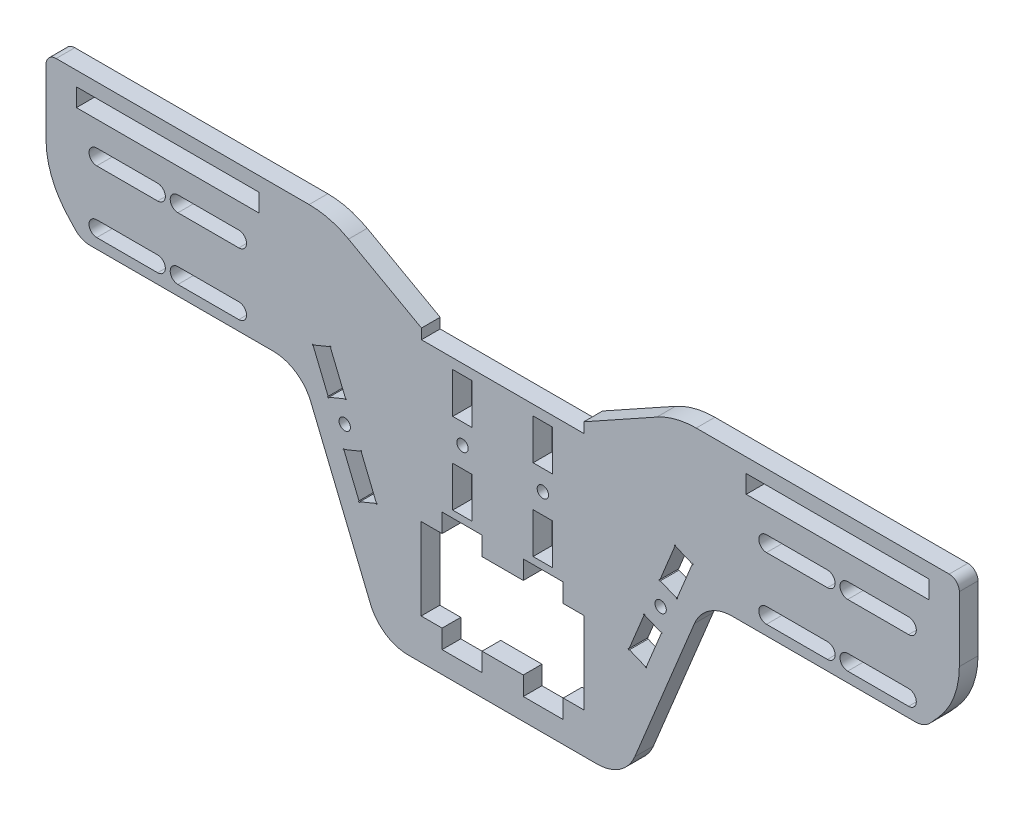
SolidWorks part; units mm, degrees
ref_plane "Front Plane" through (0, 0, 0) normal (0, 0, 1) x (1, 0, 0)
ref_plane "Top Plane" through (0, 0, 0) normal (0, 1, 0) x (1, 0, 0)
ref_plane "Right Plane" through (0, 0, 0) normal (1, 0, 0) x (0, 0, -1)
sketch "Sketch1" plane through (0, 0, 0) normal (0, 0, 1) x (1, 0, 0)
  line L0 (0, 0) -> (0, 65.275) construction
  line L1 (6.45, -12.8) -> (-6.45, -12.8)
  line L2 (12.7, -12.8) -> (12.7, -18.642) construction
  line L3 (6.45, 12.8) -> (-6.45, 12.8)
  line L4 (-25.5, -12.8) -> (-25.5, -6.25)
  line L5 (0, 12.8) -> (0, -12.8) construction
  line L6 (25.5, 0) -> (-25.5, 0) construction
  line L7 (25.4, 65.275) -> (53.975, 81.1576)
  line L8 (63.246, -20.4246) -> (127.254, -20.4246) construction
  line L9 (63.246, 24.6858) -> (127.254, 24.6858) construction
  line L10 (38.0999, -25.3999) -> (-38.0999, -25.3999)
  line L11 (95.25, 65.275) -> (-95.25, 65.275) construction
  line L12 (-95.25, 65.275) -> (-127, 65.275) construction
  line L13 (95.25, 65.275) -> (127, 65.275) construction
  line L14 (117.475, 103.375) -> (-117.475, 103.375) construction
  line L15 (95.25, 62.1) -> (-95.25, 62.1) construction
  line L16 (-171.45, 87.5) -> (-19.05, 87.5) construction
  line L17 (-171.45, 87.5) -> (-171.45, 119.25) construction
  line L18 (-171.45, 119.25) -> (-19.05, 119.25) construction
  line L19 (-19.05, 87.5) -> (-19.05, 119.25) construction
  line L20 (-95.25, 119.25) -> (-95.25, 87.5) construction
  line L21 (-171.45, 103.375) -> (-19.05, 103.375) construction
  line L22 (-18.95, 12.8) -> (-25.5, 12.8)
  line L23 (-6.45, 18.642) -> (-18.95, 18.642)
  line L24 (-6.45, 18.642) -> (-6.45, 12.8)
  line L25 (-25.5, 6.25) -> (-25.5, 12.8)
  line L26 (-18.95, 18.642) -> (-18.95, 12.8)
  line L27 (-12.7, 12.8) -> (-12.7, 18.642) construction
  line L28 (-6.45, 15.721) -> (-18.95, 15.721) construction
  line L29 (-31.342, -6.25) -> (-25.5, -6.25)
  line L30 (25.5, 12.8) -> (-25.5, 12.8) construction
  line L31 (-31.342, -6.25) -> (-31.342, 6.25)
  line L32 (-31.342, 6.25) -> (-25.5, 6.25)
  line L33 (-6.45, -15.721) -> (-18.95, -15.721) construction
  line L34 (-28.421, 6.25) -> (-28.421, -6.25) construction
  line L35 (-31.342, 0) -> (-25.5, 0) construction
  line L36 (-12.7, -12.8) -> (-12.7, -18.642) construction
  line L37 (-25.5, -12.8) -> (-25.5, 12.8) construction
  line L38 (-18.95, -18.642) -> (-18.95, -12.8)
  line L39 (-6.45, -18.642) -> (-6.45, -12.8)
  line L40 (-6.45, -18.642) -> (-18.95, -18.642)
  line L41 (-18.95, -12.8) -> (-25.5, -12.8)
  line L42 (31.342, 0) -> (25.5, 0) construction
  line L43 (25.5, -12.8) -> (-25.5, -12.8) construction
  line L44 (25.5, -12.8) -> (25.5, 12.8) construction
  line L45 (28.421, 6.25) -> (28.421, -6.25) construction
  line L46 (6.45, -15.721) -> (18.95, -15.721) construction
  line L47 (6.45, 15.721) -> (18.95, 15.721) construction
  line L48 (12.7, 12.8) -> (12.7, 18.642) construction
  line L49 (18.95, -12.8) -> (25.5, -12.8)
  line L50 (6.45, -18.642) -> (18.95, -18.642)
  line L51 (6.45, -18.642) -> (6.45, -12.8)
  line L52 (18.95, -18.642) -> (18.95, -12.8)
  line L53 (31.342, 6.25) -> (25.5, 6.25)
  line L54 (31.342, -6.25) -> (31.342, 6.25)
  line L55 (31.342, -6.25) -> (25.5, -6.25)
  line L56 (18.95, 18.642) -> (18.95, 12.8)
  line L57 (25.5, 6.25) -> (25.5, 12.8)
  line L58 (6.45, 18.642) -> (6.45, 12.8)
  line L59 (6.45, 18.642) -> (18.95, 18.642)
  line L60 (18.95, 12.8) -> (25.5, 12.8)
  line L61 (25.5, -12.8) -> (25.5, -6.25)
  line L62 (-82.55, 60.83) -> (-107.95, 60.83) construction
  line L63 (-88.9, 71.0154) -> (-101.6, 71.0154) construction
  line L64 (-88.9, 71.0154) -> (-88.9, 112.9) construction
  line L65 (-88.9, 112.9) -> (-101.6, 112.9) construction
  line L66 (-101.6, 71.0154) -> (-101.6, 112.9) construction
  line L67 (-95.25, 112.9) -> (-95.25, 71.0154) construction
  line L68 (-88.9, 91.9577) -> (-101.6, 91.9577) construction
  line L69 (-82.55, 60.83) -> (-101.6, 60.83) construction
  line L70 (-82.55, 58.417) -> (-101.6, 58.417)
  line L71 (-82.55, 63.243) -> (-101.6, 63.243)
  line L72 (-107.95, 60.83) -> (-127, 60.83) construction
  line L73 (-107.95, 58.417) -> (-127, 58.417)
  line L74 (-107.95, 63.243) -> (-127, 63.243)
  line L75 (-95.25, 73.8364) -> (-114.3, 73.8364) construction
  line L76 (74.2442, 71.0154) -> (116.2558, 71.0154) construction
  line L77 (-76.2, 71.0154) -> (-133.35, 71.0154)
  line L78 (-76.2, 71.0154) -> (-76.2, 76.6574)
  line L79 (-76.2, 76.6574) -> (-133.35, 76.6574)
  line L80 (-123.825, 70.9654) -> (-123.825, 76.7074) construction
  line L81 (-107.95, 73.8364) -> (-139.7, 73.8364) construction
  line L82 (-133.35, 71.0154) -> (-133.35, 76.6574)
  line L83 (-104.775, 76.6574) -> (-104.775, 71.0154) construction
  line L84 (-76.2, 73.8364) -> (-133.35, 73.8364) construction
  line L85 (76.2, 73.8364) -> (133.35, 73.8364) construction
  line L86 (104.775, 76.6574) -> (104.775, 71.0154) construction
  line L87 (107.95, 73.8364) -> (139.7, 73.8364) construction
  line L88 (123.825, 70.9654) -> (123.825, 76.7074) construction
  line L89 (95.25, 73.8364) -> (114.3, 73.8364) construction
  line L90 (-82.55, 41.399) -> (-101.6, 41.399) construction
  line L91 (-82.55, 38.986) -> (-101.6, 38.986)
  line L92 (-82.55, 43.812) -> (-101.6, 43.812)
  line L93 (-107.95, 41.399) -> (-127, 41.399) construction
  line L94 (-107.95, 38.986) -> (-127, 38.986)
  line L95 (-107.95, 43.812) -> (-127, 43.812)
  line L96 (25.4, 62.1) -> (-25.4, 62.1)
  line L97 (-74.2442, 24.6858) -> (-116.2558, 24.6858) construction
  line L98 (-74.2442, 24.6858) -> (-74.2442, 71.0154) construction
  line L99 (-74.2442, 71.0154) -> (-116.2558, 71.0154) construction
  line L100 (-116.2558, 24.6858) -> (-116.2558, 71.0154) construction
  line L101 (-95.25, 71.0154) -> (-95.25, 24.6858) construction
  line L102 (-74.2442, 47.8506) -> (-116.2558, 47.8506) construction
  line L103 (-63.246, -65.535) -> (-127.254, -65.535) construction
  line L104 (-63.246, -65.535) -> (-63.246, 24.6858) construction
  line L105 (-63.246, 24.6858) -> (-127.254, 24.6858) construction
  line L106 (-127.254, -65.535) -> (-127.254, 24.6858) construction
  line L107 (-95.25, 24.6858) -> (-95.25, -65.535) construction
  line L108 (-63.246, -20.4246) -> (-127.254, -20.4246) construction
  line L109 (-25.4, 62.1) -> (-25.4, 65.275)
  line L110 (-38.0999, -25.3999) -> (-63.246, 35.811)
  line L111 (-63.246, 35.811) -> (-131.9276, 35.811)
  line L112 (-142.875, 81.1576) -> (-142.875, 47.8506)
  line L113 (-131.9276, 35.811) -> (-142.875, 47.8506)
  line L114 (-142.875, 81.1576) -> (-53.975, 81.1576)
  line L115 (-25.4, 65.275) -> (-53.975, 81.1576)
  line L116 (74.2442, 47.8506) -> (116.2558, 47.8506) construction
  line L117 (38.0999, 25.3999) -> (-38.0999, 25.3999) construction
  line L118 (-38.0999, -25.3999) -> (-38.0999, 25.3999) construction
  line L119 (38.0999, -25.3999) -> (38.0999, 25.3999) construction
  line L120 (95.25, 71.0154) -> (95.25, 24.6858) construction
  line L121 (116.2558, 24.6858) -> (116.2558, 71.0154) construction
  line L122 (88.9, 71.0154) -> (101.6, 71.0154) construction
  line L123 (74.2442, 24.6858) -> (74.2442, 71.0154) construction
  line L124 (74.2442, 24.6858) -> (116.2558, 24.6858) construction
  line L125 (133.35, 71.0154) -> (133.35, 76.6574)
  line L126 (76.2, 76.6574) -> (133.35, 76.6574)
  line L127 (76.2, 71.0154) -> (76.2, 76.6574)
  line L128 (76.2, 71.0154) -> (133.35, 71.0154)
  line L129 (82.55, 60.83) -> (107.95, 60.83) construction
  line L130 (95.25, 65.275) -> (127, 65.275) construction
  line L131 (142.875, 81.1576) -> (53.975, 81.1576)
  line L132 (131.9276, 35.811) -> (142.875, 47.8506)
  line L133 (142.875, 81.1576) -> (142.875, 47.8506)
  line L134 (63.246, 35.811) -> (131.9276, 35.811)
  line L135 (38.0999, -25.3999) -> (63.246, 35.811)
  line L148 (107.95, 41.399) -> (127, 41.399) construction
  line L149 (107.95, 38.986) -> (127, 38.986)
  line L150 (107.95, 43.812) -> (127, 43.812)
  line L151 (82.55, 41.399) -> (101.6, 41.399) construction
  line L152 (82.55, 38.986) -> (101.6, 38.986)
  line L153 (82.55, 43.812) -> (101.6, 43.812)
  line L154 (107.95, 60.83) -> (127, 60.83) construction
  line L155 (107.95, 58.417) -> (127, 58.417)
  line L156 (107.95, 63.243) -> (127, 63.243)
  line L157 (82.55, 60.83) -> (101.6, 60.83) construction
  line L158 (82.55, 58.417) -> (101.6, 58.417)
  line L159 (82.55, 63.243) -> (101.6, 63.243)
  line L160 (25.4, 62.1) -> (25.4, 65.275)
  circle A0 centre (0, 103.375) radius 38.1 construction
  arc A1 (-82.55, 58.417) -> (-82.55, 63.243) centre (-82.55, 60.83) ccw
  arc A2 (-101.6, 63.243) -> (-101.6, 58.417) centre (-101.6, 60.83) ccw
  arc A3 (-107.95, 58.417) -> (-107.95, 63.243) centre (-107.95, 60.83) ccw
  arc A4 (-127, 63.243) -> (-127, 58.417) centre (-127, 60.83) ccw
  arc A5 (-82.55, 38.986) -> (-82.55, 43.812) centre (-82.55, 41.399) ccw
  arc A6 (-101.6, 43.812) -> (-101.6, 38.986) centre (-101.6, 41.399) ccw
  arc A7 (-107.95, 38.986) -> (-107.95, 43.812) centre (-107.95, 41.399) ccw
  arc A8 (-127, 43.812) -> (-127, 38.986) centre (-127, 41.399) ccw
  arc A9 (107.95, 38.986) -> (107.95, 43.812) centre (107.95, 41.399) cw
  arc A10 (127, 43.812) -> (127, 38.986) centre (127, 41.399) cw
  arc A11 (82.55, 38.986) -> (82.55, 43.812) centre (82.55, 41.399) cw
  arc A12 (101.6, 43.812) -> (101.6, 38.986) centre (101.6, 41.399) cw
  arc A13 (107.95, 58.417) -> (107.95, 63.243) centre (107.95, 60.83) cw
  arc A14 (127, 63.243) -> (127, 58.417) centre (127, 60.83) cw
  arc A15 (82.55, 58.417) -> (82.55, 63.243) centre (82.55, 60.83) cw
  arc A16 (101.6, 63.243) -> (101.6, 58.417) centre (101.6, 60.83) cw
  ellipse E0 centre (0, 103.375) end of major axis (0, 141.475) minor radius 19.05 construction
  point P0 (0, 0)
  point P9 (0, -25.3999)
  point P13 (0, 65.275)
  point P31 (0, 103.375)
  point P32 (-95.25, 103.375)
  point P38 (-12.7, 15.721)
  point P42 (-28.421, 0)
  point P54 (-12.7, -15.721)
  point P79 (12.7, -15.721)
  point P80 (28.421, 0)
  point P81 (12.7, 15.721)
  point P85 (-95.25, 91.9577)
  point P95 (-92.075, 60.83)
  point P98 (-95.25, 60.83)
  point P109 (-117.475, 60.83)
  point P110 (-123.825, 73.8364)
  point P117 (-104.775, 73.8364)
  point P122 (-104.775, 73.8864)
  point P124 (-92.075, 41.399)
  point P125 (-95.25, 47.8506)
  point P128 (-82.423, 73.8364)
  point P150 (-117.475, 41.399)
  point P160 (-95.25, -20.4246)
  point P193 (82.423, 73.8364)
  point P194 (104.775, 73.8864)
  point P201 (104.775, 73.8364)
  point P202 (123.825, 73.8364)
  point P213 (95.25, -20.4246)
  point P220 (117.475, 41.399)
  point P226 (95.25, 47.8506)
  point P233 (92.075, 41.399)
  point P241 (117.475, 60.83)
  point P246 (95.25, 60.83)
  point P248 (92.075, 60.83)
  point P255 (0, 62.1)
  dimension "D7" = 76.2
  dimension "D25" = 57.15
  dimension "D18" = 2.413
  dimension "D27" = 2
  dimension "D1" = 51
  dimension "D2" = 25.6
  dimension "D3" = 65.275
  dimension "D4" = 12.5999
  dimension "D5" = 190.5
  dimension "D6" = 31.75
  dimension "D8" = 38.1
  dimension "D9" = 31.75
  dimension "D10" = 152.4
  dimension "D12" = 5.842
  dimension "D13" = 12.5
  dimension "D14" = 12.7
  dimension "D15" = 5.842
  dimension "D16" = 12.5
  dimension "D17" = 25.4
  dimension "D19" = 12.7
  dimension "D20" = 25.4
  dimension "D21" = 19.05
  dimension "D22" = 2
  dimension "D23" = 10.1854
  dimension "D24" = 5.642
  dimension "D28" = 19.05
  dimension "D29" = 2
  dimension "D30" = 42.0116
  dimension "D31" = 46.3296
  dimension "D32" = 64.008
  dimension "D33" = 90.2208
  dimension "D34" = 25.4
  dimension "D35" = 3.175
  dimension "D36" = 4.9276
  dimension "D38" = 88.9
  dimension "D39" = 19.431
  dimension "D11" = 3.175
extrude "Boss-Extrude1" add sketch "Sketch1" along normal blind 5.842
fillet "Fillet1" radius 12.7 4 edges at (-38.0999, -25.3999, 2.921) (-63.246, 35.811, 2.921) (63.246, 35.811, 2.921) (38.0999, -25.3999, 2.921)
fillet "Fillet2" radius 6.35 2 edges at (-131.9276, 35.811, 2.921) (131.9276, 35.811, 2.921)
fillet "Fillet3" radius 25.4 2 edges at (-142.875, 47.8506, 2.921) (142.875, 47.8506, 2.921)
fillet "Fillet4" radius 3.175 2 edges at (142.875, 81.1576, 2.921) (-142.875, 81.1576, 2.921)
fillet "Fillet5" radius 25.4 2 edges at (53.975, 81.1576, 2.921) (-53.975, 81.1576, 2.921)
sketch "Sketch2" plane through (0, 0, 5.842) normal (0, 0, 1) x (1, 0, 0)
  line L0 (0, 62.1) -> (0, -25.3999) construction
  line L1 (25.4, 62.1) -> (-25.4, 62.1) construction
  line L2 (-29.5873, -25.3999) -> (29.5873, -25.3999) construction
  line L3 (25.9033, 58.925) -> (-25.9033, 58.925) construction
  line L4 (-9.525, 33.525) -> (-15.621, 33.525)
  line L5 (-9.525, 46.225) -> (-15.621, 46.225)
  line L6 (-9.525, 46.225) -> (-9.525, 58.925)
  line L7 (-9.525, 58.925) -> (-15.621, 58.925)
  line L8 (-15.621, 46.225) -> (-15.621, 58.925)
  line L9 (-9.525, 46.225) -> (-15.621, 58.925) construction
  line L10 (-9.525, 58.925) -> (-15.621, 46.225) construction
  line L11 (-15.621, 20.825) -> (-15.621, 33.525)
  line L12 (-9.525, 20.825) -> (-9.525, 33.525)
  line L13 (-9.525, 20.825) -> (-15.621, 20.825)
  line L14 (-9.525, 27.175) -> (-15.621, 27.175) construction
  line L15 (-12.573, 27.175) -> (-12.573, 52.575) construction
  line L16 (12.573, 27.175) -> (12.573, 52.575) construction
  line L17 (9.525, 27.175) -> (15.621, 27.175) construction
  line L18 (9.525, 58.925) -> (15.621, 46.225) construction
  line L19 (9.525, 46.225) -> (15.621, 58.925) construction
  line L20 (9.525, 20.825) -> (15.621, 20.825)
  line L21 (9.525, 20.825) -> (9.525, 33.525)
  line L22 (15.621, 20.825) -> (15.621, 33.525)
  line L23 (15.621, 46.225) -> (15.621, 58.925)
  line L24 (9.525, 58.925) -> (15.621, 58.925)
  line L25 (9.525, 46.225) -> (9.525, 58.925)
  line L26 (9.525, 46.225) -> (15.621, 46.225)
  line L27 (9.525, 33.525) -> (15.621, 33.525)
  circle A0 centre (-12.573, 39.875) radius 1.778
  circle A1 centre (12.573, 39.875) radius 1.778
  point P6 (-12.573, 52.575)
  point P9 (0, 58.925)
  dimension "D7" = 3.556
  dimension "D1" = 3.175
  dimension "D2" = 6.096
  dimension "D3" = 12.7
  dimension "D4" = 15.621
  dimension "D5" = 2
  dimension "D6" = 12.7
extrude "Cut-Extrude1" cut sketch "Sketch2" against normal through all
sketch "Sketch3" plane through (0, 0, 5.842) normal (0, 0, 1) x (1, 0, 0)
  line L0 (-31.342, 0) -> (-31.342, 68.5777) construction
  line L1 (-31.342, 6.25) -> (-31.342, -6.25) construction
  line L2 (-25.4, 65.275) -> (-48.2197, 77.9587) construction
  line L3 (-25.5, 19.15) -> (-25.4, 65.275) construction
  line L5 (-31.342, 31.85) -> (-25.5, 31.85)
  line L6 (-31.342, 31.85) -> (-31.342, 19.15)
  line L7 (-31.342, 19.15) -> (-25.5, 19.15)
  line L8 (-25.5, 31.85) -> (-25.5, 19.15)
  line L9 (-31.342, -6.25) -> (-25.5, -6.25) construction
  line L10 (-31.342, 44.55) -> (-25.5, 44.55)
  line L11 (-25.5, 57.25) -> (-25.5, 44.55)
  line L12 (-31.342, 57.25) -> (-31.342, 44.55)
  line L13 (-31.342, 57.25) -> (-25.5, 57.25)
  line L14 (0, 62.1) -> (0, -25.3999) construction
  line L15 (25.4, 62.1) -> (-25.4, 62.1) construction
  line L16 (-29.5873, -25.3999) -> (29.5873, -25.3999) construction
  line L17 (25.5, 19.15) -> (25.4, 65.275) construction
  line L18 (31.342, 0) -> (31.342, 68.5777) construction
  line L19 (31.342, 57.25) -> (25.5, 57.25)
  line L20 (31.342, 57.25) -> (31.342, 44.55)
  line L21 (25.5, 57.25) -> (25.5, 44.55)
  line L22 (31.342, 44.55) -> (25.5, 44.55)
  line L23 (25.5, 31.85) -> (25.5, 19.15)
  line L24 (31.342, 19.15) -> (25.5, 19.15)
  line L25 (31.342, 31.85) -> (31.342, 19.15)
  line L26 (31.342, 31.85) -> (25.5, 31.85)
  dimension "D1" = 5.842
  dimension "D2" = 12.7
  dimension "D3" = 25.4
  dimension "D4" = 2
extrude "Cut-Extrude2" [suppressed] cut sketch "Sketch3" against normal through all
sketch "Sketch4" plane through (0, 0, 5.842) normal (0, 0, 1) x (1, 0, 0)
  line L1 (25.5, 6.25) -> (31.342, 6.25)
  line L2 (25.5, 6.25) -> (25.5, -6.25)
  line L3 (25.5, -6.25) -> (31.342, -6.25)
  line L4 (31.342, 6.25) -> (31.342, -6.25)
  line L5 (-25.5, 6.25) -> (-31.342, 6.25)
  line L6 (-25.5, 6.25) -> (-25.5, -6.25)
  line L7 (-25.5, -6.25) -> (-31.342, -6.25)
  line L8 (-31.342, 6.25) -> (-31.342, -6.25)
extrude "Boss-Extrude2" add sketch "Sketch4" against normal up to surface (5.842 mm away) up to face at (12.573, 27.175, 0)
sketch "Sketch5" [suppressed] plane through (0, 0, 5.842) normal (0, 0, 1) x (1, 0, 0)
  line L0 (0, 12.8) -> (0, 62.1) construction
  line L1 (6.45, 12.8) -> (-6.45, 12.8) construction
  line L2 (25.4, 62.1) -> (-25.4, 62.1) construction
  circle A0 centre (15.621, 58.925) radius 0.1984
  circle A1 centre (15.621, 46.225) radius 0.1984
  circle A2 centre (9.525, 46.225) radius 0.1984
  circle A3 centre (9.525, 58.925) radius 0.1984
  circle A4 centre (25.5, 57.25) radius 0.1984
  circle A5 centre (31.342, 57.25) radius 0.1984
  circle A6 centre (31.342, 44.55) radius 0.1984
  circle A7 centre (25.5, 44.55) radius 0.1984
  circle A8 centre (9.525, 33.525) radius 0.1984
  circle A9 centre (15.621, 33.525) radius 0.1984
  circle A10 centre (9.525, 20.825) radius 0.1984
  circle A11 centre (15.621, 20.825) radius 0.1984
  circle A12 centre (25.5, 19.15) radius 0.1984
  circle A13 centre (18.95, 18.642) radius 0.1984
  circle A14 centre (6.45, 18.642) radius 0.1984
  circle A15 centre (25.5, 12.8) radius 0.1984
  circle A16 centre (31.342, 6.25) radius 0.1984
  circle A17 centre (31.342, -6.25) radius 0.1984
  circle A18 centre (25.5, -12.8) radius 0.1984
  circle A19 centre (18.95, -18.642) radius 0.1984
  circle A20 centre (6.45, -18.642) radius 0.1984
  circle A21 centre (31.342, 31.85) radius 0.1984
  circle A22 centre (25.5, 31.85) radius 0.1984
  circle A23 centre (31.342, 19.15) radius 0.1984
  circle A24 centre (133.35, 71.0154) radius 0.1984
  circle A25 centre (133.35, 76.6574) radius 0.1984
  circle A26 centre (76.2, 71.0154) radius 0.1984
  circle A27 centre (76.2, 76.6574) radius 0.1984
  circle A28 centre (-76.2, 76.6574) radius 0.1984
  circle A29 centre (-76.2, 71.0154) radius 0.1984
  circle A30 centre (-133.35, 76.6574) radius 0.1984
  circle A31 centre (-133.35, 71.0154) radius 0.1984
  circle A32 centre (-31.342, 19.15) radius 0.1984
  circle A33 centre (-25.5, 31.85) radius 0.1984
  circle A34 centre (-31.342, 31.85) radius 0.1984
  circle A35 centre (-6.45, -18.642) radius 0.1984
  circle A36 centre (-18.95, -18.642) radius 0.1984
  circle A37 centre (-25.5, -12.8) radius 0.1984
  circle A38 centre (-31.342, -6.25) radius 0.1984
  circle A39 centre (-31.342, 6.25) radius 0.1984
  circle A40 centre (-25.5, 12.8) radius 0.1984
  circle A41 centre (-6.45, 18.642) radius 0.1984
  circle A42 centre (-18.95, 18.642) radius 0.1984
  circle A43 centre (-25.5, 19.15) radius 0.1984
  circle A44 centre (-15.621, 20.825) radius 0.1984
  circle A45 centre (-9.525, 20.825) radius 0.1984
  circle A46 centre (-15.621, 33.525) radius 0.1984
  circle A47 centre (-9.525, 33.525) radius 0.1984
  circle A48 centre (-25.5, 44.55) radius 0.1984
  circle A49 centre (-31.342, 44.55) radius 0.1984
  circle A50 centre (-31.342, 57.25) radius 0.1984
  circle A51 centre (-25.5, 57.25) radius 0.1984
  circle A52 centre (-9.525, 58.925) radius 0.1984
  circle A53 centre (-9.525, 46.225) radius 0.1984
  circle A54 centre (-15.621, 46.225) radius 0.1984
  circle A55 centre (-15.621, 58.925) radius 0.1984
  dimension "D1" = 0.3969
  dimension "D2" = 0.3969
  dimension "D3" = 0.3969
  dimension "D4" = 0.3969
  dimension "D5" = 0.3969
  dimension "D6" = 0.3969
  dimension "D7" = 0.3969
  dimension "D8" = 0.3969
  dimension "D9" = 0.3969
  dimension "D10" = 0.3969
  dimension "D11" = 0.3969
  dimension "D12" = 0.3969
  dimension "D13" = 0.3969
  dimension "D14" = 0.3969
  dimension "D15" = 0.3969
  dimension "D16" = 0.3969
  dimension "D17" = 0.3969
  dimension "D18" = 0.3969
  dimension "D19" = 0.3969
  dimension "D20" = 0.3969
  dimension "D21" = 0.3969
  dimension "D22" = 0.3969
  dimension "D23" = 0.3969
  dimension "D24" = 0.3969
  dimension "D25" = 0.3969
  dimension "D26" = 0.3969
  dimension "D27" = 0.3969
  dimension "D28" = 0.3969
extrude "Cut-Extrude3" [suppressed] cut sketch "Sketch5" against normal through all
sketch "Sketch6" plane through (0, 0, 5.842) normal (0, 0, 1) x (1, 0, 0)
  line L1 (49.7039, 20.2257) -> (44.3001, 22.4456)
  line L2 (32.5242, -13.9064) -> (51.2007, 31.5563)
  line L3 (32.5242, -13.9064) -> (51.2007, 31.5563) construction
  line L4 (44.8779, 8.4783) -> (39.4741, 10.6983)
  line L5 (44.8779, 8.4783) -> (49.7039, 20.2257)
  line L6 (39.4741, 10.6983) -> (44.3001, 22.4456)
  line L7 (49.126, 34.193) -> (53.952, 45.9403)
  line L8 (59.3557, 43.7204) -> (53.952, 45.9403)
  line L9 (54.5298, 31.973) -> (59.3557, 43.7204)
  line L10 (54.5298, 31.973) -> (49.126, 34.193)
  line L11 (0, 62.1) -> (0, -25.3999) construction
  line L12 (25.4, 62.1) -> (-25.4, 62.1) construction
  line L13 (-29.5873, -25.3999) -> (29.5873, -25.3999) construction
  line L14 (-32.5242, -13.9064) -> (-51.2007, 31.5563) construction
  line L15 (-54.5298, 31.973) -> (-49.126, 34.193)
  line L16 (-54.5298, 31.973) -> (-59.3557, 43.7204)
  line L17 (-59.3557, 43.7204) -> (-53.952, 45.9403)
  line L18 (-49.126, 34.193) -> (-53.952, 45.9403)
  line L19 (-39.4741, 10.6983) -> (-44.3001, 22.4456)
  line L20 (-44.8779, 8.4783) -> (-49.7039, 20.2257)
  line L21 (-44.8779, 8.4783) -> (-39.4741, 10.6983)
  line L22 (-49.7039, 20.2257) -> (-44.3001, 22.4456)
  circle A0 centre (49.4149, 27.2093) radius 1.778
  circle A1 centre (53.952, 45.9403) radius 0.1984
  circle A2 centre (59.3557, 43.7204) radius 0.1984
  circle A3 centre (54.5298, 31.973) radius 0.1984
  circle A4 centre (49.126, 34.193) radius 0.1984
  circle A5 centre (44.8779, 8.4783) radius 0.1984
  circle A6 centre (39.4741, 10.6983) radius 0.1984
  circle A7 centre (44.3001, 22.4456) radius 0.1984
  circle A8 centre (49.7039, 20.2257) radius 0.1984
  circle A9 centre (-49.7039, 20.2257) radius 0.1984
  circle A10 centre (-44.3001, 22.4456) radius 0.1984
  circle A11 centre (-39.4741, 10.6983) radius 0.1984
  circle A12 centre (-44.8779, 8.4783) radius 0.1984
  circle A13 centre (-49.126, 34.193) radius 0.1984
  circle A14 centre (-54.5298, 31.973) radius 0.1984
  circle A15 centre (-59.3557, 43.7204) radius 0.1984
  circle A16 centre (-53.952, 45.9403) radius 0.1984
  circle A17 centre (-49.4149, 27.2093) radius 1.778
  point P5 (47.002, 21.3357)
  point P29 (-47.002, 21.3357)
  dimension "D6" = 3.556
  dimension "D8" = 0.3969
  dimension "D9" = 0.3969
  dimension "D10" = 0.3969
  dimension "D11" = 0.3969
  dimension "D12" = 0.3969
  dimension "D13" = 0.3969
  dimension "D14" = 0.3969
  dimension "D15" = 0.3969
  dimension "D2" = 5.842
  dimension "D4" = 25.4
  dimension "D7" = 6.35
  dimension "D1" = 9.525
  dimension "D3" = 12.7
  dimension "D5" = 2
extrude "Cut-Extrude4" cut sketch "Sketch6" against normal through all contours A4 L10 A3 L9 A2 L8 A1 L7 | L10 A4 L7 | L7 A4 L10 | L9 A3 L10 | L10 A3 L9 | L7 A1 L8 | L8 A2 L9 | L9 A2 L8 | L8 A1 L7 | A8 L1 A7 L6 A6 L4 A5 L5 | A0 | L5 A5 L4 | L4 A5 L5 | L6 A6 L4 | L4 A6 L6 | L1 A7 L6 | L6 A7 L1 | L1 A8 L5 | L5 A8 L1
sketch "Sketch7" plane through (0, 0, 5.842) normal (0, 0, 1) x (1, 0, 0)
  line L0 (0, 62.1) -> (0, -12.8) construction
  line L1 (25.4, 62.1) -> (-25.4, 62.1) construction
  line L2 (-6.45, -12.8) -> (6.45, -12.8) construction
ref_plane "Plane1" through (0, 0, 0) normal (-1, 0, 0) x (0, -1, 0)
mirror "Mirror1" about plane through (0, 0, 0) normal (-1, 0, 0) of "Cut-Extrude4"
sketch "Sketch8" [suppressed] plane through (0, 0, 5.842) normal (0, 0, 1) x (1, 0, 0)
  line L0 (0, 33.525) -> (0, 46.225) construction
  line L1 (0, 62.1) -> (0, -12.8) construction
  line L2 (-3.9687, 33.525) -> (-3.9687, 46.225)
  line L3 (3.9688, 33.525) -> (3.9688, 46.225)
  line L4 (25.4, 62.1) -> (-25.4, 62.1) construction
  arc A0 (-3.9687, 33.525) -> (3.9688, 33.525) centre (0, 33.525) ccw
  arc A1 (3.9688, 46.225) -> (-3.9687, 46.225) centre (0, 46.225) ccw
  point P4 (0, 39.875)
  dimension "D1" = 3.9688
  dimension "D2" = 12.7
  dimension "D3" = 15.875
extrude "Cut-Extrude5" [suppressed] cut sketch "Sketch8" against normal through all
